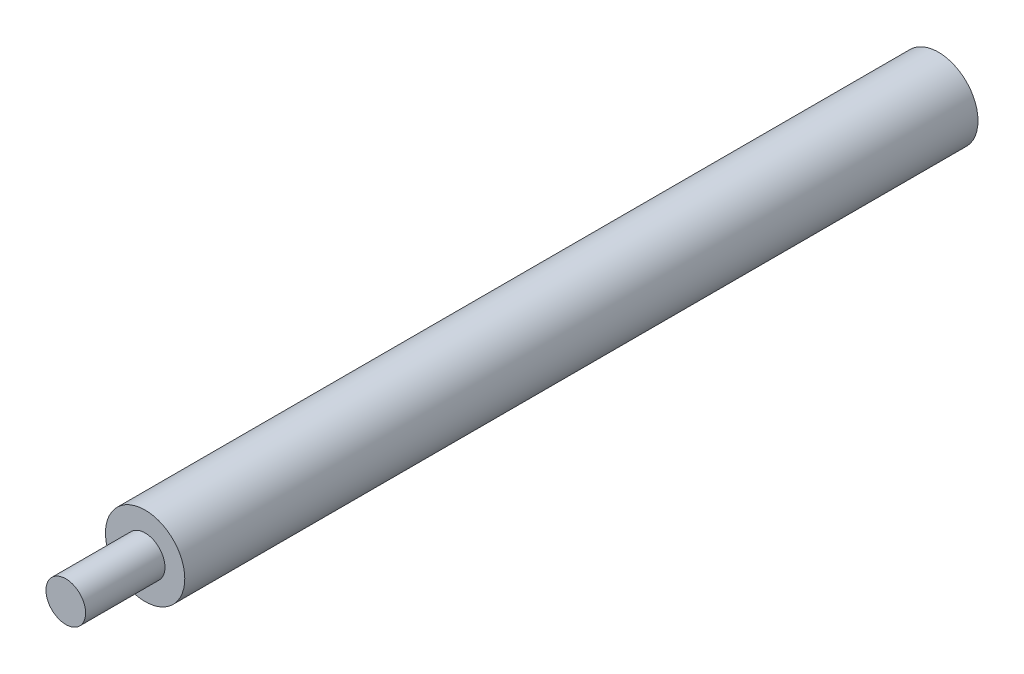
SolidWorks part; units mm, degrees
ref_plane "Front Plane" through (0, 0, 0) normal (0, 0, 1) x (1, 0, 0)
ref_plane "Top Plane" through (0, 0, 0) normal (0, 1, 0) x (1, 0, 0)
ref_plane "Right Plane" through (0, 0, 0) normal (1, 0, 0) x (0, 0, -1)
sketch "Sketch1" plane through (0, 0, 0) normal (0, 0, 1) x (1, 0, 0)
  circle A1 centre (0, 0) radius 2.5
  dimension "D2" = 5
extrude "Boss-Extrude1" add sketch "Sketch1" along normal blind 50
sketch "Sketch2" plane through (0, 0, 50) normal (0, 0, 1) x (1, 0, 0)
  circle A0 centre (0, 0) radius 1.25
  dimension "D1" = 2.5
extrude "Boss-Extrude2" add sketch "Sketch2" along normal blind 5
sketch "Sketch3" plane through (0, 0, 0) normal (0, 0, -1) x (-1, 0, 0)
  circle A0 centre (0, 0) radius 1.25
  dimension "D1" = 2.5
extrude "Cut-Extrude1" cut sketch "Sketch3" against normal blind 5
